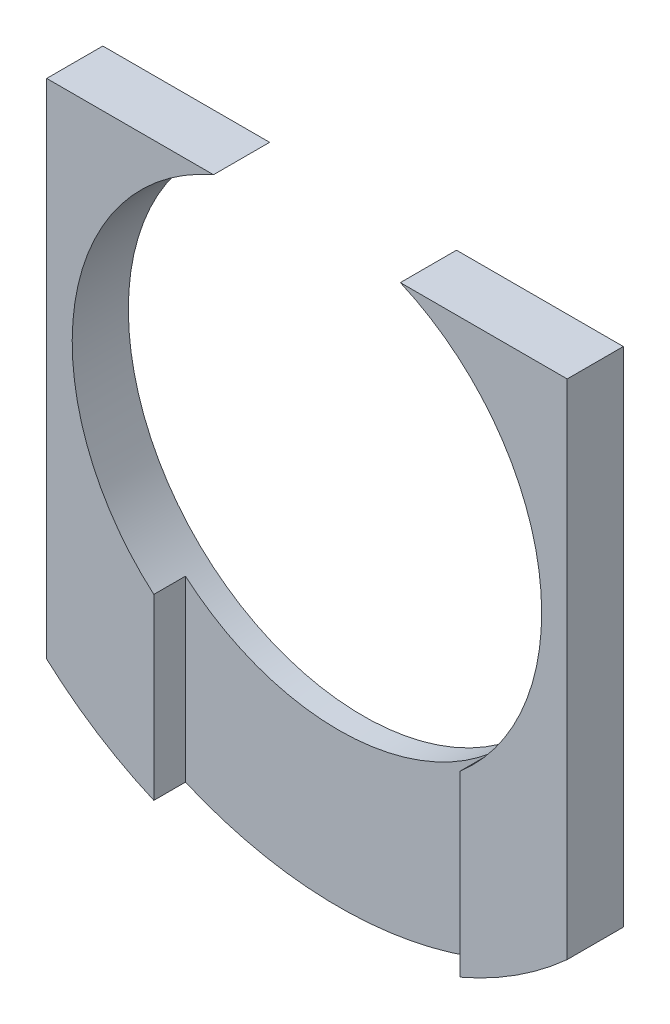
SolidWorks part; units mm, degrees
ref_plane "Front Plane" through (0, 0, 0) normal (0, 0, 1) x (1, 0, 0)
ref_plane "Top Plane" through (0, 0, 0) normal (0, 1, 0) x (1, 0, 0)
ref_plane "Right Plane" through (0, 0, 0) normal (1, 0, 0) x (0, 0, -1)
ref_plane "PZ_p30_100" through (0, 0, 30.1) normal (0, 0, 1) x (1, 0, 0)
sketch "S_cyl1" plane through (0, 0, 30.1) normal (0, 0, 1) x (1, 0, 0)
  circle A0 centre (0, 0) radius 19
  dimension "D1_S_cyl1" = 38
extrude "Boss_1" add sketch "S_cyl1" along normal blind 2.75
ref_plane "PZ_p30_000" through (0, 0, 30) normal (0, 0, 1) x (1, 0, 0)
sketch "S_hole2" plane through (0, 0, 30) normal (0, 0, 1) x (1, 0, 0)
  circle A0 centre (0, 0) radius 11.5
  dimension "D1_S_hole2" = 23
extrude "Hole_2" cut sketch "S_hole2" along normal blind 2.95
sketch "S_cut3" plane through (0, 0, 30) normal (0, 0, 1) x (1, 0, 0)
  line L0 (12.75, -20) -> (20, -20)
  line L1 (20, -20) -> (20, 20)
  line L2 (20, 20) -> (12.75, 20)
  line L3 (12.75, 20) -> (12.75, -20)
  dimension "P1" = 12.75
  dimension "P2" = 20
  dimension "P3" = 20
  dimension "P4" = 20
  dimension "P5" = 20
  dimension "P6" = 20
  dimension "P7" = 12.75
  dimension "P8" = 20
extrude "Pocket_3" cut sketch "S_cut3" along normal blind 2.95
sketch "S_cut4" plane through (0, 0, 30) normal (0, 0, 1) x (1, 0, 0)
  line L0 (-20, -20) -> (-12.75, -20)
  line L1 (-12.75, -20) -> (-12.75, 20)
  line L2 (-12.75, 20) -> (-20, 20)
  line L3 (-20, 20) -> (-20, -20)
  dimension "P1" = 20
  dimension "P2" = 20
  dimension "P3" = 12.75
  dimension "P4" = 20
  dimension "P5" = 12.75
  dimension "P6" = 20
  dimension "P7" = 20
  dimension "P8" = 20
extrude "Pocket_4" cut sketch "S_cut4" along normal blind 2.95
sketch "S_cut5" plane through (0, 0, 30) normal (0, 0, 1) x (1, 0, 0)
  line L0 (-20, 10.55) -> (20, 10.55)
  line L1 (20, 10.55) -> (20, 20)
  line L2 (20, 20) -> (-20, 20)
  line L3 (-20, 20) -> (-20, 10.55)
  dimension "P1" = 20
  dimension "P2" = 10.55
  dimension "P3" = 20
  dimension "P4" = 10.55
  dimension "P5" = 20
  dimension "P6" = 20
  dimension "P7" = 20
  dimension "P8" = 20
extrude "Pocket_5" cut sketch "S_cut5" along normal blind 2.95
ref_plane "PZ_p31_300" through (0, 0, 31.3) normal (0, 0, 1) x (1, 0, 0)
sketch "S_cut6" plane through (0, 0, 31.3) normal (0, 0, 1) x (1, 0, 0)
  line L0 (-7.5, -20) -> (7.5, -20)
  line L1 (7.5, -20) -> (7.5, -8.1)
  line L2 (7.5, -8.1) -> (-7.5, -8.1)
  line L3 (-7.5, -8.1) -> (-7.5, -20)
  dimension "P1" = 7.5
  dimension "P2" = 20
  dimension "P3" = 7.5
  dimension "P4" = 20
  dimension "P5" = 7.5
  dimension "P6" = 8.1
  dimension "P7" = 7.5
  dimension "P8" = 8.1
extrude "Pocket_6" cut sketch "S_cut6" along normal blind 1.65
equation "\"plate_t\" = 3"
equation "\"clearance\" = 0.5"
